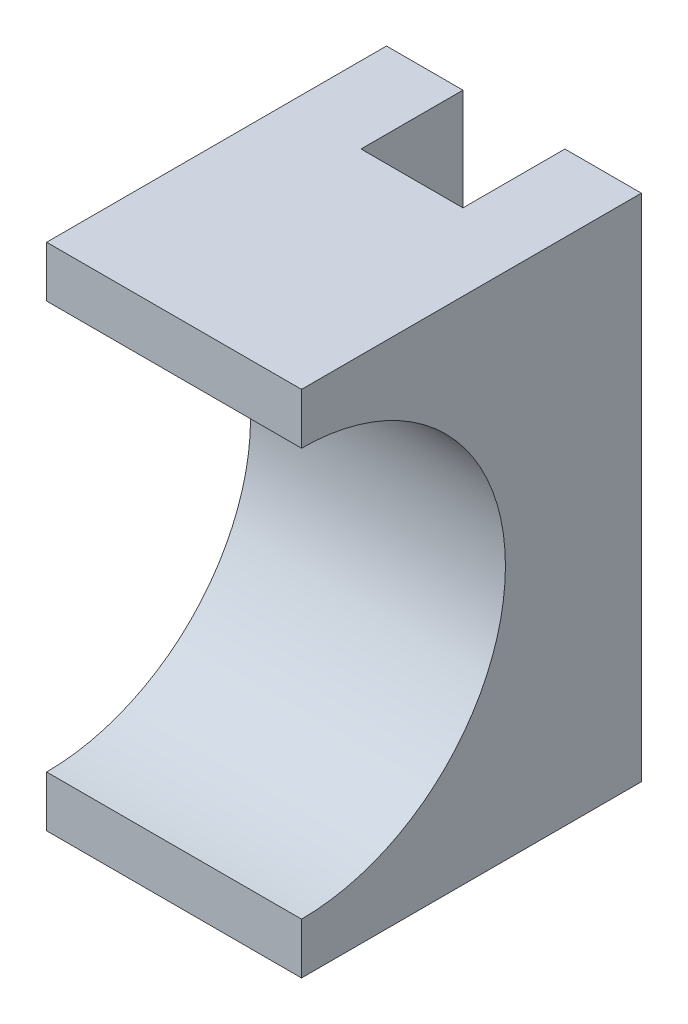
SolidWorks part; units mm, degrees
ref_plane "Front Plane" through (0, 0, 0) normal (0, 0, 1) x (1, 0, 0)
ref_plane "Top Plane" through (0, 0, 0) normal (0, 1, 0) x (1, 0, 0)
ref_plane "Right Plane" through (0, 0, 0) normal (1, 0, 0) x (0, 0, -1)
sketch "Sketch1" plane through (0, 0, 0) normal (0, 1, 0) x (1, 0, 0)
  line L4 (-7.5, 10) -> (7.5, 10)
  line L5 (-7.5, 10) -> (-7.5, -10)
  line L6 (-7.5, -10) -> (7.5, -10)
  line L7 (7.5, 10) -> (7.5, -10)
  point P5 (0, -10)
  point P6 (-7.5, 0)
  dimension "D2" = 20
  dimension "D1" = 15
extrude "Boss-Extrude1" add sketch "Sketch1" along normal blind 30
sketch "Sketch2" plane through (7.5, 0, 0) normal (1, 0, 0) x (0, 0, -1)
  line L1 (-10, 30) -> (-10, 0) construction
  line L2 (10, 30) -> (10, 0) construction
  line L3 (-10, 3) -> (-10, 27)
  arc A0 (-10, 27) -> (-10, 3) centre (-10, 15) cw
  point P14 (10, 15)
  dimension "D1" = 12
extrude "Cut-Extrude1" cut sketch "Sketch2" against normal up to next
sketch "Sketch4" plane through (0, 30, 0) normal (0, 1, 0) x (1, 0, 0)
  line L0 (7.5, 10) -> (-7.5, 10) construction
  line L1 (3, 10) -> (-3, 10)
  line L2 (3, 10) -> (3, 4)
  line L3 (3, 4) -> (-3, 4)
  line L4 (-3, 10) -> (-3, 4)
  point P6 (0, 4)
  dimension "D1" = 6
  dimension "D2" = 6
extrude "Cut-Extrude4" cut sketch "Sketch4" against normal blind 25
sketch "Sketch3" plane through (0, 30, 0) normal (0, 1, 0) x (1, 0, 0)
  line L0 (7.5, 10) -> (3, 10) construction
  circle A0 centre (0, 7) radius 1.1
  dimension "D1" = 2.2
  dimension "D2" = 3
extrude "Cut-Extrude2" cut sketch "Sketch3" against normal up to next
